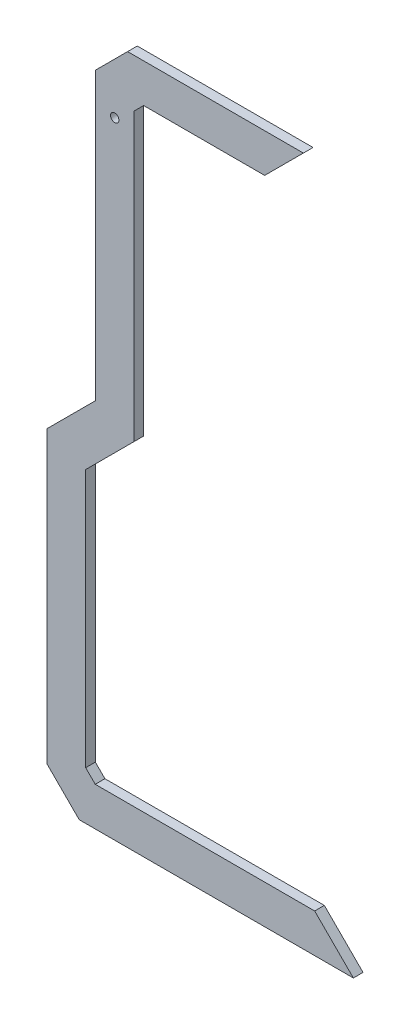
SolidWorks part; units mm, degrees
ref_plane "Front Plane" through (0, 0, 0) normal (0, 0, 1) x (1, 0, 0)
ref_plane "Top Plane" through (0, 0, 0) normal (0, 1, 0) x (1, 0, 0)
ref_plane "Right Plane" through (0, 0, 0) normal (1, 0, 0) x (0, 0, -1)
sketch "Sketch1" plane through (0, 0, 0) normal (0, 0, 1) x (1, 0, 0)
  line L0 (70, -179.754) -> (-15, -179.754) construction
  line L1 (-15, -179.754) -> (-25, -169.754) construction
  line L2 (-25, -169.754) -> (-25, -79.754) construction
  line L3 (-25, -79.754) -> (-10, -64.754) construction
  line L4 (-10, -64.754) -> (-10, 24.0035) construction
  line L5 (-10, 24.0035) -> (0, 34.0035) construction
  line L6 (0, 34.0035) -> (70, 34.0035) construction
  line L7 (70, -179.754) -> (-15, -179.754)
  line L8 (-15, -179.754) -> (-25, -169.754)
  line L9 (-25, -169.754) -> (-25, -79.754)
  line L10 (-25, -79.754) -> (-10, -64.754)
  line L11 (-10, -64.754) -> (-10, 24.0035)
  line L12 (-10, 24.0035) -> (0, 34.0035)
  line L13 (0, 34.0035) -> (54.5, 34.0035)
  line L15 (42.5, 22.0035) -> (4.9706, 22.0035)
  line L16 (4.9706, 22.0035) -> (2, 19.033)
  line L17 (2, 19.033) -> (2, -69.7245)
  line L18 (2, -69.7245) -> (-13, -84.7245)
  line L19 (-13, -84.7245) -> (-13, -164.7834)
  line L20 (-13, -164.7834) -> (-10.0294, -167.754)
  line L21 (-10.0294, -167.754) -> (58, -167.754)
  line L22 (58, -167.754) -> (70, -179.754)
  line L23 (54.5, 34.0035) -> (42.5, 22.0035)
  circle A1 centre (-4, 14.2435) radius 1.3
  point P2 (54.5, 34.0035)
  dimension "D1" = 12
  dimension "D2" = 12
  dimension "D3" = 12
  dimension "D4" = 12
  dimension "D5" = 12
  dimension "D6" = 12
  dimension "D7" = 12
  dimension "D8" = 45
  dimension "D9" = 54.5
  dimension "D10" = 45
extrude "Extrude1" add sketch "Sketch1" along normal blind 3
